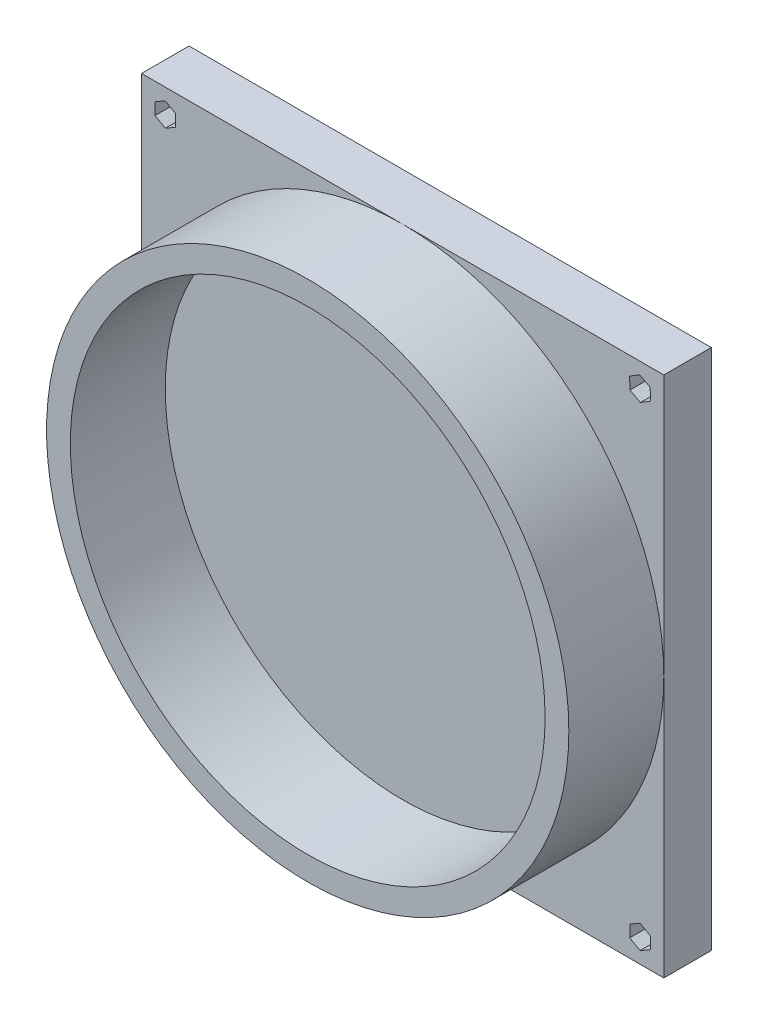
SolidWorks part; units mm, degrees
ref_plane "Front Plane" through (0, 0, 0) normal (0, 0, 1) x (1, 0, 0)
ref_plane "Top Plane" through (0, 0, 0) normal (0, 1, 0) x (1, 0, 0)
ref_plane "Right Plane" through (0, 0, 0) normal (1, 0, 0) x (0, 0, -1)
sketch "Sketch2" plane through (0, 0, 0) normal (0, 0, 1) x (1, 0, 0)
  line L1 (-60, 60) -> (60, 60)
  line L2 (-60, 60) -> (-60, -60)
  line L3 (-60, -60) -> (60, -60)
  line L4 (60, 60) -> (60, -60)
  circle A0 centre (0, 0) radius 55
  point P7 (0, -60)
  dimension "D1" = 110
  dimension "D2" = 60
  dimension "D3" = 60
  dimension "D4" = 60
  dimension "D5" = 60
extrude "Boss-Extrude2" add sketch "Sketch2" along normal blind 30 contours A0
sketch "Sketch5" plane through (0, 0, 30) normal (0, 0, 1) x (1, 0, 0)
  circle A0 centre (0, 0) radius 50
  dimension "D1" = 100
extrude "Cut-Extrude2" cut sketch "Sketch5" against normal blind 21
sketch "Sketch6" plane through (0, 0, 0) normal (0, 0, 1) x (1, 0, 0)
  line L1 (55, 55) -> (-55, 55)
  line L2 (55, 55) -> (55, -55)
  line L3 (55, -55) -> (-55, -55)
  line L4 (-55, 55) -> (-55, -55)
  dimension "D1" = 110
  dimension "D2" = 110
  dimension "D3" = 55
  dimension "D4" = 55
extrude "Boss-Extrude3" add sketch "Sketch6" along normal blind 10
sketch "Sketch7" plane through (0, 0, 0) normal (0, 0, 1) x (1, 0, 0)
  line L0 (-55, 55) -> (-55, 0) construction
  line L1 (-47.8268, 48.7642) -> (-47.8431, 51.2641)
  line L2 (-47.8431, 51.2641) -> (-50.0163, 52.4999)
  line L3 (-50.0163, 52.4999) -> (-52.1732, 51.2358)
  line L4 (-52.1732, 51.2358) -> (-52.1569, 48.7359)
  line L5 (-52.1569, 48.7359) -> (-49.9837, 47.5001)
  line L6 (-49.9837, 47.5001) -> (-47.8268, 48.7642)
  line L7 (0, 55) -> (-55, 55) construction
  line L8 (55, 55) -> (0, 55) construction
  line L9 (50.0806, 47.5013) -> (52.2042, 48.8205)
  line L10 (52.2042, 48.8205) -> (52.1236, 51.3192)
  line L11 (52.1236, 51.3192) -> (49.9194, 52.4987)
  line L12 (49.9194, 52.4987) -> (47.7958, 51.1795)
  line L13 (47.7958, 51.1795) -> (47.8764, 48.6808)
  line L14 (47.8764, 48.6808) -> (50.0806, 47.5013)
  line L15 (55, 0) -> (55, 55) construction
  line L16 (0, -55) -> (55, -55) construction
  line L17 (52.1651, -51.25) -> (52.1651, -48.75)
  line L18 (52.1651, -48.75) -> (50, -47.5)
  line L19 (50, -47.5) -> (47.8349, -48.75)
  line L20 (47.8349, -48.75) -> (47.8349, -51.25)
  line L21 (47.8349, -51.25) -> (50, -52.5)
  line L22 (50, -52.5) -> (52.1651, -51.25)
  line L23 (55, -55) -> (55, 0) construction
  line L24 (-55, 0) -> (-55, -55) construction
  line L25 (-49.9848, -52.5) -> (-47.8274, -51.2368)
  line L26 (-47.8274, -51.2368) -> (-47.8426, -48.7369)
  line L27 (-47.8426, -48.7369) -> (-50.0152, -47.5)
  line L28 (-50.0152, -47.5) -> (-52.1726, -48.7632)
  line L29 (-52.1726, -48.7632) -> (-52.1574, -51.2631)
  line L30 (-52.1574, -51.2631) -> (-49.9848, -52.5)
  line L31 (-55, -55) -> (0, -55) construction
  circle A0 centre (-50, 50) radius 2.1651 construction
  circle A1 centre (50, 50) radius 2.1651 construction
  circle A2 centre (50, -50) radius 2.1651 construction
  circle A3 centre (-50, -50) radius 2.1651 construction
  dimension "D1" = 5
  dimension "D2" = 5
  dimension "D3" = 2.5
  dimension "D4" = 5
  dimension "D5" = 5
  dimension "D6" = 2.5
  dimension "D7" = 5
  dimension "D8" = 5
  dimension "D9" = 2.5
  dimension "D10" = 5
  dimension "D11" = 5
  dimension "D12" = 100
  dimension "D13" = 100
  dimension "D14" = 2.5
  dimension "D15" = 2.5
  dimension "D16" = 2.5
extrude "Cut-Extrude5" cut sketch "Sketch7" along normal blind 23
sketch "Sketch8" plane through (0, 0, 10) normal (0, 0, 1) x (1, 0, 0)
  line L0 (49.9194, 52.4987) -> (52.1236, 51.3192)
